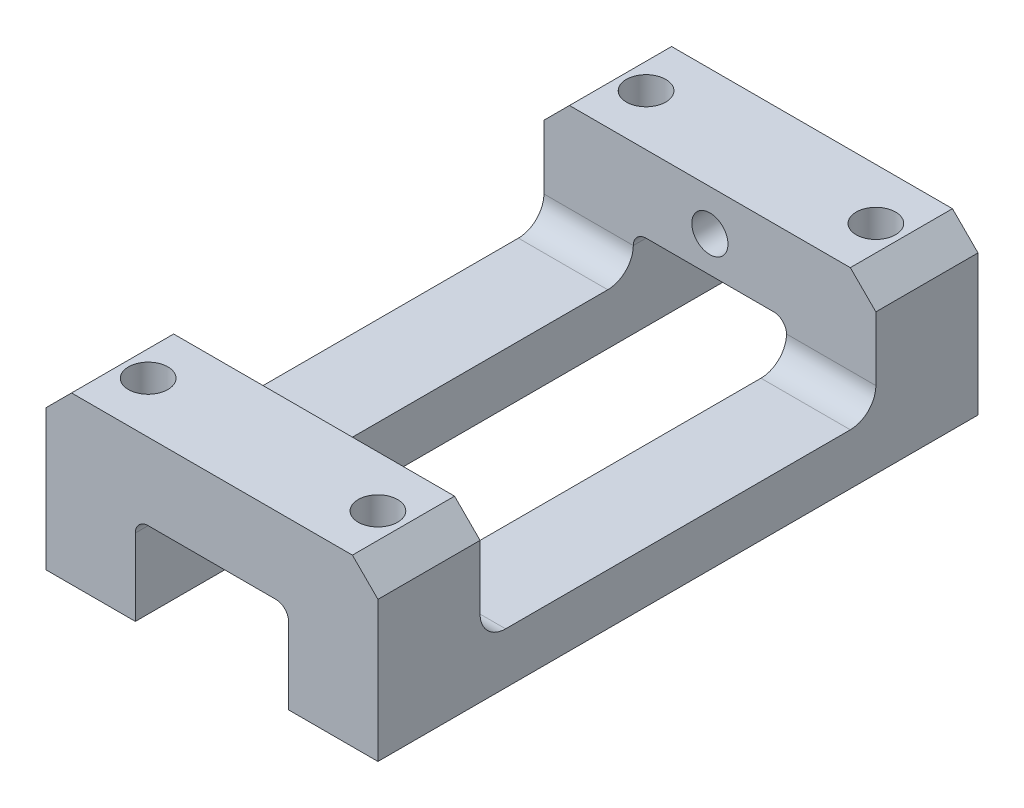
SolidWorks part; units mm, degrees
material "6061-T6 (SS)"
ref_plane "Front Plane" through (0, 0, 0) normal (0, 0, 1) x (1, 0, 0)
ref_plane "Top Plane" through (0, 0, 0) normal (0, 1, 0) x (1, 0, 0)
ref_plane "Right Plane" through (0, 0, 0) normal (1, 0, 0) x (0, 0, -1)
sketch "Sketch1" plane through (0, 0, 0) normal (0, 0, 1) x (1, 0, 0)
  line L0 (-41.275, 0) -> (-19.05, 0)
  line L1 (-41.275, -41.275) -> (41.275, -41.275) construction
  line L2 (-41.275, 0) -> (-41.275, 41.275)
  line L3 (-41.275, 41.275) -> (41.275, 41.275)
  line L4 (41.275, 0) -> (41.275, 41.275)
  line L5 (-41.275, -41.275) -> (41.275, 41.275) construction
  line L6 (-41.275, 41.275) -> (41.275, -41.275) construction
  line L7 (-41.275, -41.275) -> (-41.275, 0) construction
  line L8 (41.275, -41.275) -> (41.275, 0) construction
  line L9 (-19.05, 0) -> (0, 0) construction
  line L10 (19.05, 0) -> (41.275, 0)
  line L11 (0, 0) -> (19.05, 0) construction
  line L13 (-19.05, 0) -> (19.05, 0)
  line L14 (-19.05, 0) -> (-19.05, 19.05)
  line L15 (-15.875, 22.225) -> (15.875, 22.225)
  line L16 (19.05, 0) -> (19.05, 19.05)
  line L17 (0, 22.225) -> (0, 0) construction
  line L18 (-19.05, 9.525) -> (19.05, 9.525) construction
  arc A0 (19.05, 0) -> (-19.05, 0) centre (0, 0) ccw construction
  arc A1 (13.4704, -13.4704) -> (19.05, 0) centre (0, 0) ccw construction
  arc A2 (-13.4704, -13.4704) -> (13.4704, -13.4704) centre (0, 0) ccw construction
  arc A3 (-19.05, 0) -> (-13.4704, -13.4704) centre (0, 0) ccw construction
  arc A4 (15.875, 22.225) -> (19.05, 19.05) centre (15.875, 19.05) cw
  arc A5 (-19.05, 19.05) -> (-15.875, 22.225) centre (-15.875, 19.05) cw
  point P0 (0, 0)
  point P18 (19.05, 22.225)
  point P323 (0, 9.525)
  dimension "D2" = 38.1
  dimension "D5" = 3.175
  dimension "D1" = 82.55
  dimension "D3" = 82.55
  dimension "D4" = 22.225
extrude "Boss-Extrude1" add sketch "Sketch1" along normal blind 149.225 contours L14 A5 L15 A4 L16 L10 L4 L3 L2 L0
chamfer "Chamfer1" distance 6.35 angle 45 2 edges at (41.275, 41.275, 74.6125) (-41.275, 41.275, 74.6125)
sketch "Sketch2" plane through (0, 41.275, 0) normal (0, 1, 0) x (1, 0, 0)
  line L1 (-28.575, -136.525) -> (28.575, -136.525) construction
  line L2 (-28.575, -136.525) -> (-28.575, -12.7) construction
  line L3 (-28.575, -12.7) -> (28.575, -12.7) construction
  line L4 (28.575, -136.525) -> (28.575, -12.7) construction
  line L5 (-28.575, -136.525) -> (28.575, -12.7) construction
  line L6 (-28.575, -12.7) -> (28.575, -136.525) construction
  point P1 (28.575, -12.7)
  point P2 (-28.575, -136.525)
  point P3 (-28.575, -12.7)
  point P4 (28.575, -136.525)
  point P19 (0, -12.7)
  dimension "D1" = 57.15
  dimension "D2" = 123.825
  dimension "D3" = 12.7
hole_wizard "3/8 Clearance Hole1" positions "Sketch2" profile "Sketch3" hole size "3/8" standard "ANSI Inch" end condition through all
sketch "Sketch3" plane through (28.575, 41.275, 12.7) normal (1, 0, 0) x (0, 0, 1)
  line L0 (0, 0) -> (0, 41.275)
  line L1 (0, 41.275) -> (4.9022, 41.275)
  line L2 (4.9022, 41.275) -> (4.9022, 0)
  line L5 (4.9022, 0) -> (0, 0)
  line L11 (0, -6.35) -> (0, 107.95) construction
  dimension "Thru Hole Dia." = 9.8044
  dimension "Thru Hole Depth" = 41.275
sketch "Sketch4" plane through (-41.275, 0, 0) normal (-1, 0, 0) x (0, 0, 1)
  line L0 (0, 41.275) -> (149.225, 41.275) construction
  line L1 (25.4, 41.275) -> (123.825, 41.275)
  line L2 (25.4, 41.275) -> (25.4, 12.7)
  line L3 (25.4, 12.7) -> (123.825, 12.7)
  line L4 (123.825, 41.275) -> (123.825, 12.7)
  line L5 (74.6125, 12.7) -> (74.6125, 41.275) construction
  line L6 (25.4, 26.9875) -> (123.825, 26.9875) construction
  line L7 (149.225, 0) -> (149.225, 34.925) construction
  line L8 (149.225, 0) -> (0, 0) construction
  point P10 (74.6125, 0)
  point P264 (74.6125, 26.9875)
  dimension "D2" = 25.4
  dimension "D3" = 12.7
extrude "Cut-Extrude1" cut sketch "Sketch4" against normal through all
fillet "Fillet1" radius 6.35 4 edges at (30.1625, 12.7, 25.4) (30.1625, 12.7, 123.825) (-30.1625, 12.7, 123.825) (-30.1625, 12.7, 25.4)
sketch "Sketch5" plane through (0, 0, 149.225) normal (0, 0, 1) x (1, 0, 0)
  line L0 (-15.875, 22.225) -> (15.875, 22.225) construction
  circle A0 centre (0, 31.115) radius 4.5
  point P4 (0, 0)
  dimension "D1" = 9
  dimension "D2" = 8.89
extrude "Cut-Extrude2" cut sketch "Sketch5" against normal blind 40.64 from surface at -123.825 starting at face at (0, 27.4365, 25.4)
